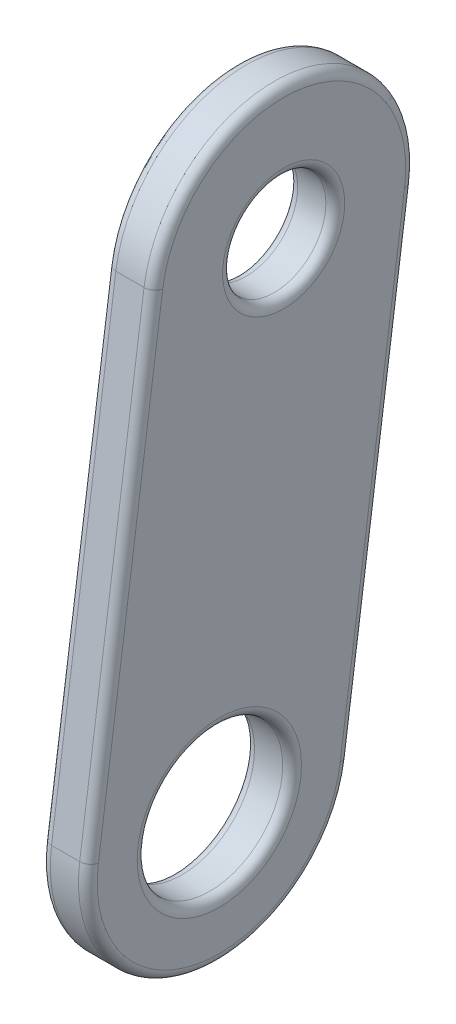
SolidWorks part; units mm, degrees
material "AISI 4130 Steel, normalized at 870C"
ref_plane "Front Plane" through (0, 0, 0) normal (1, 0, 0) x (0, 1, 0)
ref_plane "Top Plane" through (0, 0, 0) normal (0, 0, 1) x (0, 1, 0)
ref_plane "Right Plane" through (0, 0, 0) normal (0, 1, 0) x (-1, 0, 0)
sketch "Sketch1" plane through (0, 0, 0) normal (1, 0, 0) x (0, 1, 0)
  line L0 (0, 25.0173) -> (0, -29.3781) construction
  line L1 (-117.7626, 0) -> (83.2469, 0) construction
  line L2 (-49.5286, 6.85) -> (0, 0) construction
  line L3 (-47.6106, 20.718) -> (1.918, 13.868)
  line L4 (-51.4466, -7.018) -> (-1.918, -13.868)
  arc A0 (-47.6106, 20.718) -> (-51.4466, -7.018) centre (-49.5286, 6.85) ccw
  arc A1 (-1.918, -13.868) -> (1.918, 13.868) centre (0, 0) ccw
  circle A2 centre (-49.5286, 6.85) radius 2.5
  circle A3 centre (0, 0) radius 2.5
  point P7 (-24.7643, 3.425)
  dimension "D1" = 5
  dimension "D2" = 14
  dimension "D5" = 14
  dimension "D3" = 50
  dimension "D4" = 6.85
extrude "Boss-Extrude1" add sketch "Sketch1" along normal mid plane 5 contours L4 A1 L3 A0
sketch "Sketch2" plane through (2.5, 0, 0) normal (1, 0, 0) x (0, 1, 0)
  point P0 (-49.5286, 6.85)
  point P1 (0, 0)
hole_wizard "M14 Clearance Hole1" positions "Sketch2" profile "Sketch3" hole size "M14" standard "ISO"
sketch "Sketch3" plane through (2.5, -49.5286, 6.85) normal (0, 1, 0) x (0, 0, -1)
  line L0 (0, 0) -> (0, 5)
  line L1 (0, 5) -> (7.75, 5)
  line L2 (7.75, 5) -> (7.75, 0)
  line L5 (7.75, 0) -> (0, 0)
  line L11 (0, -6.35) -> (0, 107.95) construction
  dimension "Thru Hole Dia." = 15.5
  dimension "Thru Hole Depth" = 5
sketch "Sketch4" plane through (2.5, 0, 0) normal (1, 0, 0) x (0, 1, 0)
  point P0 (0, 0)
hole_wizard "M10 Clearance Hole1" positions "Sketch4" profile "Sketch5" hole size "M10" standard "ISO" end condition through all
sketch "Sketch5" plane through (2.5, 0, 0) normal (0, 1, 0) x (0, 0, -1)
  line L0 (0, 0) -> (0, 5)
  line L1 (0, 5) -> (5.5, 5)
  line L2 (5.5, 5) -> (5.5, 0)
  line L5 (5.5, 0) -> (0, 0)
  line L11 (0, -6.35) -> (0, 107.95) construction
  dimension "Thru Hole Dia." = 11
  dimension "Thru Hole Depth" = 5
fillet "Fillet1" radius 1 12 edges at (-2.5, 13.868, -1.918) (-2.5, -26.6823, -10.443) (-2.5, -63.3965, 8.768) (2.5, 13.868, -1.918) (2.5, -26.6823, -10.443) (2.5, -63.3965, 8.768) (-2.5, -22.8463, 17.293) (2.5, -22.8463, 17.293) (2.5, -49.5286, -0.9) (-2.5, -49.5286, -0.9) (-2.5, 0, -5.5) (2.5, 0, -5.5)
